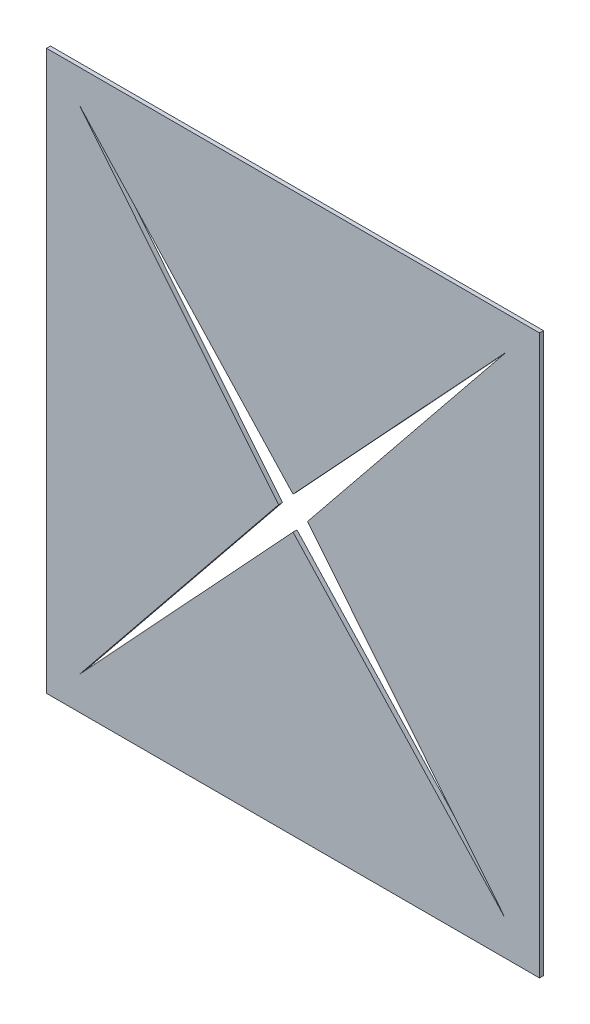
SolidWorks part; units mm, degrees
material "POLYURETHANE (11671)"
ref_plane "Front Plane" through (0, 0, 0) normal (0, 0, 1) x (1, 0, 0)
ref_plane "Top Plane" through (0, 0, 0) normal (0, 1, 0) x (1, 0, 0)
ref_plane "Right Plane" through (0, 0, 0) normal (1, 0, 0) x (0, 0, -1)
sketch "Sketch1" plane through (0, 0, 0) normal (0, 0, 1) x (1, 0, 0)
  line L0 (-41.275, 47.625) -> (-41.275, -47.625)
  line L1 (-47.625, 53.975) -> (47.625, 53.975)
  line L2 (-47.625, 53.975) -> (-47.625, -53.975)
  line L3 (-47.625, -53.975) -> (47.625, -53.975)
  line L4 (47.625, 53.975) -> (47.625, -53.975)
  line L5 (-47.625, 53.975) -> (47.625, -53.975) construction
  line L6 (-47.625, -53.975) -> (47.625, 53.975) construction
  line L7 (-2.8015, 3.175) -> (2.8015, 3.175)
  line L8 (-2.8015, 3.175) -> (-2.8015, -3.175)
  line L9 (-2.8015, -3.175) -> (2.8015, -3.175)
  line L10 (2.8015, 3.175) -> (2.8015, -3.175)
  line L11 (-2.8015, 3.175) -> (2.8015, -3.175) construction
  line L12 (-2.8015, -3.175) -> (2.8015, 3.175) construction
  line L13 (-41.275, -47.625) -> (41.275, -47.625)
  line L14 (41.275, 47.625) -> (41.275, -47.625)
  line L15 (-41.275, 47.625) -> (41.275, 47.625)
  line L16 (41.275, -47.625) -> (0, -3.175)
  line L17 (0, -3.175) -> (-41.275, -47.625)
  line L18 (41.275, -47.625) -> (2.8015, 0)
  line L19 (2.8015, 0) -> (41.275, 47.625)
  line L20 (41.275, 47.625) -> (0, 3.175)
  line L21 (0, 3.175) -> (-41.275, 47.625)
  line L22 (-41.275, 47.625) -> (-2.8015, 0)
  line L23 (-2.8015, 0) -> (-41.275, -47.625)
  point P0 (0, 0)
  point P6 (0, 0)
  dimension "D2" = 95.25
  dimension "D3" = 82.55
  dimension "D4" = 6.35
  dimension "D1" = 6.35
extrude "Boss-Extrude1" add sketch "Sketch1" along normal blind 0.762 contours L4 L1 L2 L3 L0 L15 L14 L13 | L23 L22 L0 | L21 L20 L15 | L19 L18 L14 | L16 L17 L13
